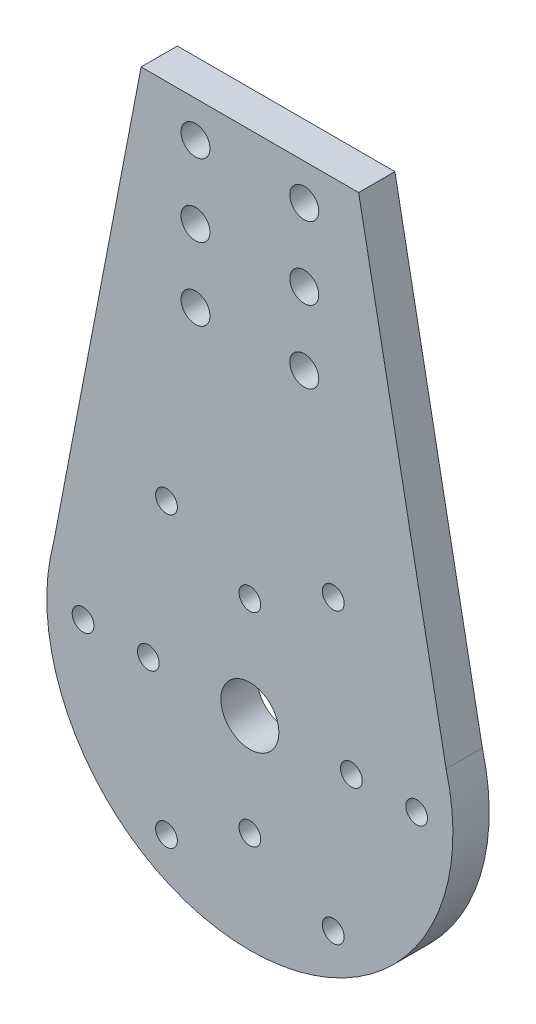
SolidWorks part; units mm, degrees
material "Acrylic (Medium-high impact)"
ref_plane "Front Plane" through (0, 0, 0) normal (0, 0, 1) x (1, 0, 0)
ref_plane "Top Plane" through (0, 0, 0) normal (0, 1, 0) x (1, 0, 0)
ref_plane "Right Plane" through (0, 0, 0) normal (1, 0, 0) x (0, 0, -1)
sketch "Sketch1" plane through (0, 0, 0) normal (0, 0, 1) x (1, 0, 0)
  line L0 (0, 0) -> (0, 102.4347) construction
  line L3 (-15, 70) -> (15, 70)
  line L6 (-53.7823, 0) -> (57.6054, 0) construction
  line L7 (57.6054, 0) -> (0, 0) construction
  line L8 (0, 0) -> (28.5913, 49.5216) construction
  line L9 (28.5913, 49.5216) -> (0, 0) construction
  line L10 (0, 0) -> (25.2625, -43.7558) construction
  line L11 (25.2625, -43.7558) -> (-22.2856, 38.5998) construction
  line L12 (-22.2856, 38.5998) -> (0, 0) construction
  line L13 (0, 0) -> (-22.4095, -38.8144) construction
  line L14 (-15, 70) -> (-27.0622, 7.186)
  line L15 (15, 70) -> (27.0622, 7.186)
  line L16 (0, 0) -> (0, -37.4282) construction
  circle A0 centre (0, 0) radius 28
  circle A1 centre (0, 0) radius 14 construction
  arc A3 (-28, 0) -> (28, 0) centre (0, 0) cw
  circle A4 centre (0, 0) radius 23 construction
  circle A5 centre (23, 0) radius 1.5
  circle A6 centre (11.5, 19.9186) radius 1.5
  circle A7 centre (-11.5, 19.9186) radius 1.5
  circle A8 centre (-23, 0) radius 1.5
  circle A9 centre (-11.5, -19.9186) radius 1.5
  circle A10 centre (11.5, -19.9186) radius 1.5
  arc A11 (-27.0622, 7.186) -> (27.0622, 7.186) centre (0, 0) cw
  circle A12 centre (7.5, 65) radius 2
  circle A13 centre (7.5, 55) radius 2
  circle A14 centre (-7.5, 65) radius 2
  circle A15 centre (-7.5, 55) radius 2
  circle A18 centre (0, 0) radius 4
  circle A19 centre (0, 14) radius 1.5
  circle A20 centre (14, 0) radius 1.5
  circle A21 centre (0, -14) radius 1.5
  circle A22 centre (-14, 0) radius 1.5
  circle A23 centre (-7.5, 45) radius 2
  circle A24 centre (7.5, 45) radius 2
  dimension "D1" = 30
  dimension "D2" = 28
  dimension "D3" = 56
  dimension "D6" = 60
  dimension "D8" = 7.5
  dimension "D12" = 10
  dimension "D4" = 15
  dimension "D5" = 70
  dimension "D7" = 60
  dimension "D9" = 7.5
  dimension "D10" = 7.5
  dimension "D11" = 7.5
  dimension "D13" = 10
  dimension "D14" = 5
  dimension "D15" = 10
  dimension "D17" = 5
  dimension "D18" = 10
extrude "Boss-Extrude1" add sketch "Sketch1" along normal blind 5
